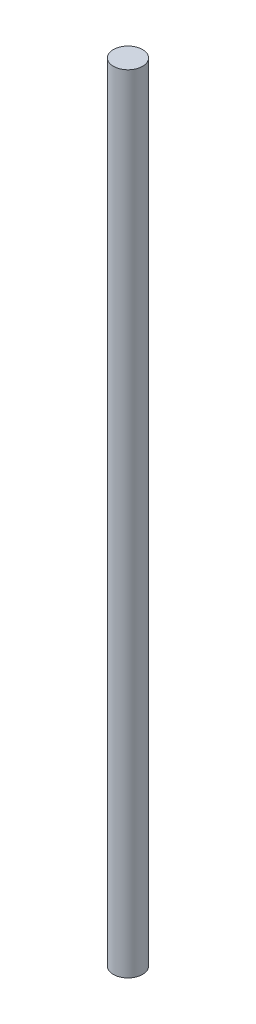
SolidWorks part; units mm, degrees
ref_plane "Front Plane" through (0, 0, 0) normal (0, 0, 1) x (1, 0, 0)
ref_plane "Top Plane" through (0, 0, 0) normal (0, 1, 0) x (1, 0, 0)
ref_plane "Right Plane" through (0, 0, 0) normal (1, 0, 0) x (0, 0, -1)
sketch "Sketch1" plane through (0, 0, 0) normal (0, 1, 0) x (1, 0, 0)
  circle A0 centre (0, 0) radius 0.5
extrude "Boss-Extrude1" add sketch "Sketch1" along normal blind 27 contours A0
